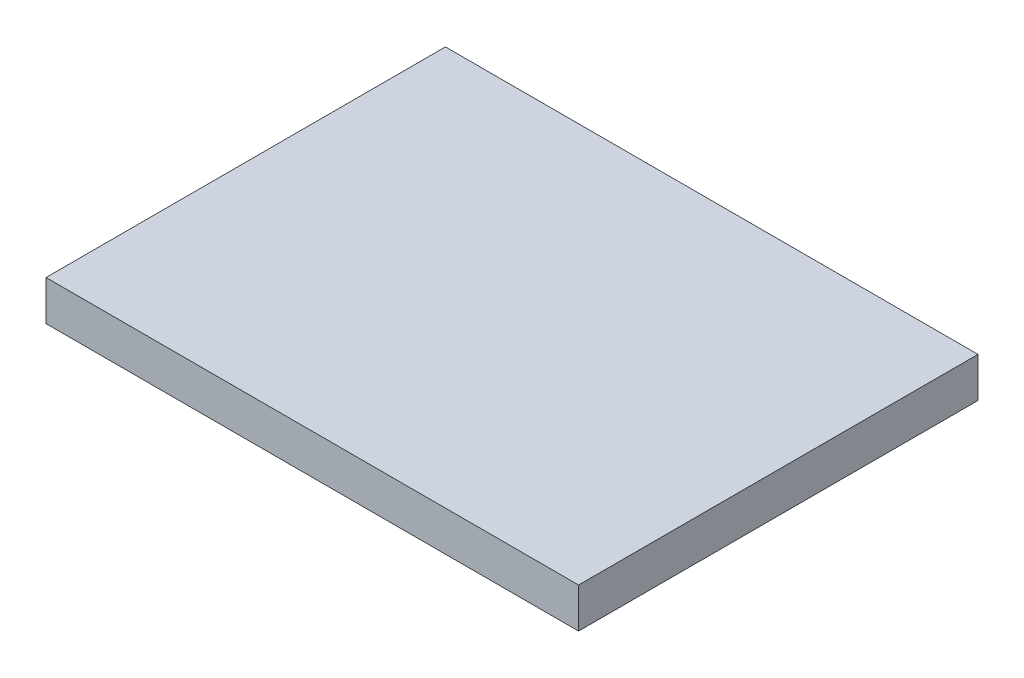
SolidWorks part; units mm, degrees
ref_plane "Piano frontale" through (0, 0, 0) normal (0, 0, 1) x (1, 0, 0)
ref_plane "Piano superiore" through (0, 0, 0) normal (0, 1, 0) x (1, 0, 0)
ref_plane "Piano destro" through (0, 0, 0) normal (1, 0, 0) x (0, 0, -1)
sketch "Sketch1" plane through (0, 0, 0) normal (0, 0, 1) x (1, 0, 0)
  line L1 (-128.788, 533.9944) -> (271.212, 533.9944)
  line L2 (-128.788, 533.9944) -> (-128.788, 503.9944)
  line L3 (-128.788, 503.9944) -> (271.212, 503.9944)
  line L4 (271.212, 533.9944) -> (271.212, 503.9944)
  dimension "D1" = 30
  dimension "D2" = 400
extrude "Boss-Extrude1" add sketch "Sketch1" along normal mid plane 300
sketch "Sketch2" plane through (0, 533.9944, 0) normal (0, 1, 0) x (1, 0, 0)
  line L0 (-128.788, 0) -> (271.212, 0)
  line L1 (-128.788, 150) -> (-128.788, -150) construction
  line L2 (271.212, 150) -> (271.212, -150) construction
  line L3 (71.212, 0) -> (71.212, -150)
  line L4 (271.212, -150) -> (-128.788, -150) construction
  line L5 (71.212, 0) -> (71.212, 150)
  line L6 (271.212, 150) -> (-128.788, 150) construction
